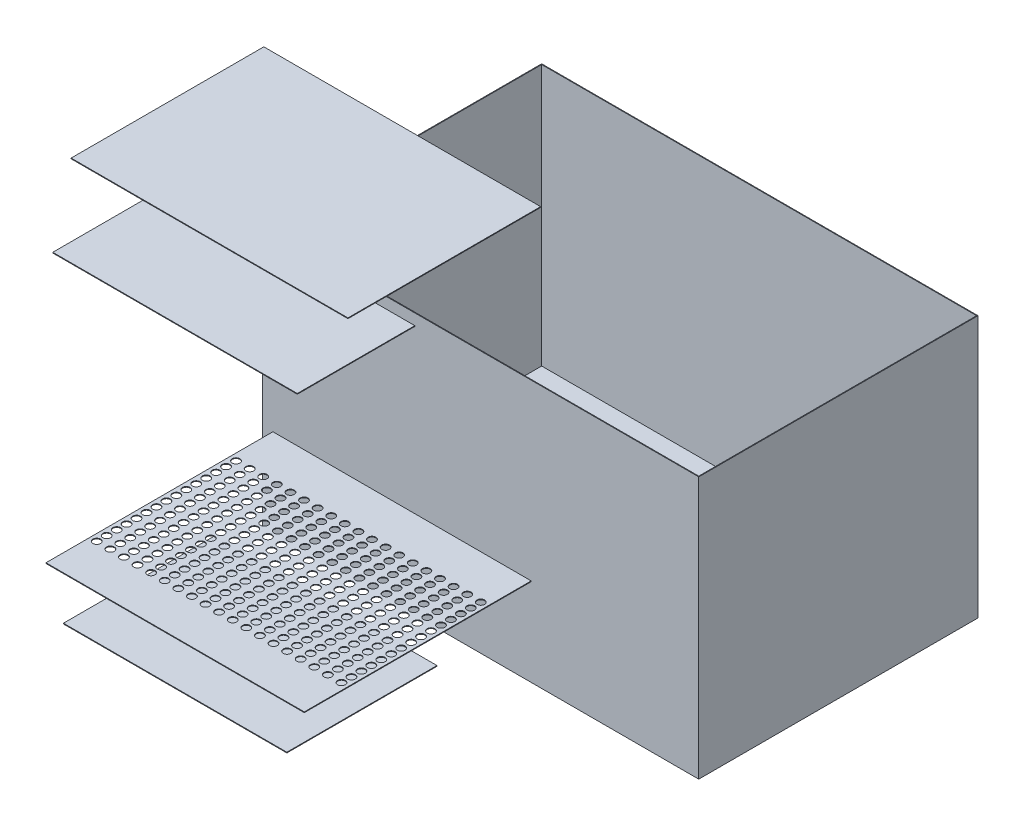
SolidWorks part; units mm, degrees
ref_plane "Спереди" through (0, 0, 0) normal (0, 0, 1) x (1, 0, 0)
ref_plane "Сверху" through (0, 0, 0) normal (0, 1, 0) x (1, 0, 0)
ref_plane "Справа" through (0, 0, 0) normal (1, 0, 0) x (0, 0, -1)
sketch "MASTER_FOOTPRINT" plane through (0, 0, 0) normal (0, 1, 0) x (1, 0, 0)
  line L1 (0, 0) -> (1250, 0)
  line L2 (0, 0) -> (0, 800)
  line L3 (0, 800) -> (1250, 800)
  line L4 (1250, 0) -> (1250, 800)
  dimension "D1" = 1250
  dimension "D2" = 800
extrude "BATH_BASE_PLATE" add sketch "MASTER_FOOTPRINT" along normal blind 750
shell "BATH_SHELL_2MM" thickness 2
sketch "Эскиз1" plane through (0, 0, 0) normal (0, 1, 0) x (1, 0, 0)
  line L1 (80, -220) -> (720, -220)
  line L2 (80, -220) -> (80, -650)
  line L3 (80, -650) -> (720, -650)
  line L4 (720, -220) -> (720, -650)
extrude "INLET_IMPACT_BAFFLE" add sketch "Эскиз1" along normal blind 2 from offset 125 separate body
sketch "Эскиз2" plane through (0, 0, 0) normal (0, 1, 0) x (1, 0, 0)
  line L0 (2, 2) -> (1248, 2) construction
  line L1 (30, 2) -> (770, 2)
  line L2 (30, 2) -> (30, -650)
  line L3 (30, -650) -> (770, -650)
  line L4 (770, 2) -> (770, -650)
  circle A0 centre (49.4737, -125) radius 11
  circle A1 centre (49.4737, -153.5) radius 11
  circle A2 centre (49.4737, -182) radius 11
  circle A3 centre (49.4737, -210.5) radius 11
  circle A4 centre (49.4737, -239) radius 11
  circle A5 centre (49.4737, -267.5) radius 11
  circle A6 centre (49.4737, -296) radius 11
  circle A7 centre (49.4737, -324.5) radius 11
  circle A8 centre (49.4737, -353) radius 11
  circle A9 centre (49.4737, -381.5) radius 11
  circle A10 centre (49.4737, -410) radius 11
  circle A11 centre (49.4737, -438.5) radius 11
  circle A12 centre (49.4737, -467) radius 11
  circle A13 centre (49.4737, -495.5) radius 11
  circle A14 centre (49.4737, -524) radius 11
  circle A15 centre (88.4211, -125) radius 11
  circle A16 centre (88.4211, -153.5) radius 11
  circle A17 centre (88.4211, -182) radius 11
  circle A18 centre (88.4211, -210.5) radius 11
  circle A19 centre (88.4211, -239) radius 11
  circle A20 centre (88.4211, -267.5) radius 11
  circle A21 centre (88.4211, -296) radius 11
  circle A22 centre (88.4211, -324.5) radius 11
  circle A23 centre (88.4211, -353) radius 11
  circle A24 centre (88.4211, -381.5) radius 11
  circle A25 centre (88.4211, -410) radius 11
  circle A26 centre (88.4211, -438.5) radius 11
  circle A27 centre (88.4211, -467) radius 11
  circle A28 centre (88.4211, -495.5) radius 11
  circle A29 centre (88.4211, -524) radius 11
  circle A30 centre (127.3684, -125) radius 11
  circle A31 centre (127.3684, -153.5) radius 11
  circle A32 centre (127.3684, -182) radius 11
  circle A33 centre (127.3684, -210.5) radius 11
  circle A34 centre (127.3684, -239) radius 11
  circle A35 centre (127.3684, -267.5) radius 11
  circle A36 centre (127.3684, -296) radius 11
  circle A37 centre (127.3684, -324.5) radius 11
  circle A38 centre (127.3684, -353) radius 11
  circle A39 centre (127.3684, -381.5) radius 11
  circle A40 centre (127.3684, -410) radius 11
  circle A41 centre (127.3684, -438.5) radius 11
  circle A42 centre (127.3684, -467) radius 11
  circle A43 centre (127.3684, -495.5) radius 11
  circle A44 centre (127.3684, -524) radius 11
  circle A45 centre (166.3158, -125) radius 11
  circle A46 centre (166.3158, -153.5) radius 11
  circle A47 centre (166.3158, -182) radius 11
  circle A48 centre (166.3158, -210.5) radius 11
  circle A49 centre (166.3158, -239) radius 11
  circle A50 centre (166.3158, -267.5) radius 11
  circle A51 centre (166.3158, -296) radius 11
  circle A52 centre (166.3158, -324.5) radius 11
  circle A53 centre (166.3158, -353) radius 11
  circle A54 centre (166.3158, -381.5) radius 11
  circle A55 centre (166.3158, -410) radius 11
  circle A56 centre (166.3158, -438.5) radius 11
  circle A57 centre (166.3158, -467) radius 11
  circle A58 centre (166.3158, -495.5) radius 11
  circle A59 centre (166.3158, -524) radius 11
  circle A60 centre (205.2632, -125) radius 11
  circle A61 centre (205.2632, -153.5) radius 11
  circle A62 centre (205.2632, -182) radius 11
  circle A63 centre (205.2632, -210.5) radius 11
  circle A64 centre (205.2632, -239) radius 11
  circle A65 centre (205.2632, -267.5) radius 11
  circle A66 centre (205.2632, -296) radius 11
  circle A67 centre (205.2632, -324.5) radius 11
  circle A68 centre (205.2632, -353) radius 11
  circle A69 centre (205.2632, -381.5) radius 11
  circle A70 centre (205.2632, -410) radius 11
  circle A71 centre (205.2632, -438.5) radius 11
  circle A72 centre (205.2632, -467) radius 11
  circle A73 centre (205.2632, -495.5) radius 11
  circle A74 centre (205.2632, -524) radius 11
  circle A75 centre (244.2105, -125) radius 11
  circle A76 centre (244.2105, -153.5) radius 11
  circle A77 centre (244.2105, -182) radius 11
  circle A78 centre (244.2105, -210.5) radius 11
  circle A79 centre (244.2105, -239) radius 11
  circle A80 centre (244.2105, -267.5) radius 11
  circle A81 centre (244.2105, -296) radius 11
  circle A82 centre (244.2105, -324.5) radius 11
  circle A83 centre (244.2105, -353) radius 11
  circle A84 centre (244.2105, -381.5) radius 11
  circle A85 centre (244.2105, -410) radius 11
  circle A86 centre (244.2105, -438.5) radius 11
  circle A87 centre (244.2105, -467) radius 11
  circle A88 centre (244.2105, -495.5) radius 11
  circle A89 centre (244.2105, -524) radius 11
  circle A90 centre (283.1579, -125) radius 11
  circle A91 centre (283.1579, -153.5) radius 11
  circle A92 centre (283.1579, -182) radius 11
  circle A93 centre (283.1579, -210.5) radius 11
  circle A94 centre (283.1579, -239) radius 11
  circle A95 centre (283.1579, -267.5) radius 11
  circle A96 centre (283.1579, -296) radius 11
  circle A97 centre (283.1579, -324.5) radius 11
  circle A98 centre (283.1579, -353) radius 11
  circle A99 centre (283.1579, -381.5) radius 11
  circle A100 centre (283.1579, -410) radius 11
  circle A101 centre (283.1579, -438.5) radius 11
  circle A102 centre (283.1579, -467) radius 11
  circle A103 centre (283.1579, -495.5) radius 11
  circle A104 centre (283.1579, -524) radius 11
  circle A105 centre (322.1053, -125) radius 11
  circle A106 centre (322.1053, -153.5) radius 11
  circle A107 centre (322.1053, -182) radius 11
  circle A108 centre (322.1053, -210.5) radius 11
  circle A109 centre (322.1053, -239) radius 11
  circle A110 centre (322.1053, -267.5) radius 11
  circle A111 centre (322.1053, -296) radius 11
  circle A112 centre (322.1053, -324.5) radius 11
  circle A113 centre (322.1053, -353) radius 11
  circle A114 centre (322.1053, -381.5) radius 11
  circle A115 centre (322.1053, -410) radius 11
  circle A116 centre (322.1053, -438.5) radius 11
  circle A117 centre (322.1053, -467) radius 11
  circle A118 centre (322.1053, -495.5) radius 11
  circle A119 centre (322.1053, -524) radius 11
  circle A120 centre (361.0526, -125) radius 11
  circle A121 centre (361.0526, -153.5) radius 11
  circle A122 centre (361.0526, -182) radius 11
  circle A123 centre (361.0526, -210.5) radius 11
  circle A124 centre (361.0526, -239) radius 11
  circle A125 centre (361.0526, -267.5) radius 11
  circle A126 centre (361.0526, -296) radius 11
  circle A127 centre (361.0526, -324.5) radius 11
  circle A128 centre (361.0526, -353) radius 11
  circle A129 centre (361.0526, -381.5) radius 11
  circle A130 centre (361.0526, -410) radius 11
  circle A131 centre (361.0526, -438.5) radius 11
  circle A132 centre (361.0526, -467) radius 11
  circle A133 centre (361.0526, -495.5) radius 11
  circle A134 centre (361.0526, -524) radius 11
  circle A135 centre (400, -125) radius 11
  circle A136 centre (400, -153.5) radius 11
  circle A137 centre (400, -182) radius 11
  circle A138 centre (400, -210.5) radius 11
  circle A139 centre (400, -239) radius 11
  circle A140 centre (400, -267.5) radius 11
  circle A141 centre (400, -296) radius 11
  circle A142 centre (400, -324.5) radius 11
  circle A143 centre (400, -353) radius 11
  circle A144 centre (400, -381.5) radius 11
  circle A145 centre (400, -410) radius 11
  circle A146 centre (400, -438.5) radius 11
  circle A147 centre (400, -467) radius 11
  circle A148 centre (400, -495.5) radius 11
  circle A149 centre (400, -524) radius 11
  circle A150 centre (438.9474, -125) radius 11
  circle A151 centre (438.9474, -153.5) radius 11
  circle A152 centre (438.9474, -182) radius 11
  circle A153 centre (438.9474, -210.5) radius 11
  circle A154 centre (438.9474, -239) radius 11
  circle A155 centre (438.9474, -267.5) radius 11
  circle A156 centre (438.9474, -296) radius 11
  circle A157 centre (438.9474, -324.5) radius 11
  circle A158 centre (438.9474, -353) radius 11
  circle A159 centre (438.9474, -381.5) radius 11
  circle A160 centre (438.9474, -410) radius 11
  circle A161 centre (438.9474, -438.5) radius 11
  circle A162 centre (438.9474, -467) radius 11
  circle A163 centre (438.9474, -495.5) radius 11
  circle A164 centre (438.9474, -524) radius 11
  circle A165 centre (477.8947, -125) radius 11
  circle A166 centre (477.8947, -153.5) radius 11
  circle A167 centre (477.8947, -182) radius 11
  circle A168 centre (477.8947, -210.5) radius 11
  circle A169 centre (477.8947, -239) radius 11
  circle A170 centre (477.8947, -267.5) radius 11
  circle A171 centre (477.8947, -296) radius 11
  circle A172 centre (477.8947, -324.5) radius 11
  circle A173 centre (477.8947, -353) radius 11
  circle A174 centre (477.8947, -381.5) radius 11
  circle A175 centre (477.8947, -410) radius 11
  circle A176 centre (477.8947, -438.5) radius 11
  circle A177 centre (477.8947, -467) radius 11
  circle A178 centre (477.8947, -495.5) radius 11
  circle A179 centre (477.8947, -524) radius 11
  circle A180 centre (516.8421, -125) radius 11
  circle A181 centre (516.8421, -153.5) radius 11
  circle A182 centre (516.8421, -182) radius 11
  circle A183 centre (516.8421, -210.5) radius 11
  circle A184 centre (516.8421, -239) radius 11
  circle A185 centre (516.8421, -267.5) radius 11
  circle A186 centre (516.8421, -296) radius 11
  circle A187 centre (516.8421, -324.5) radius 11
  circle A188 centre (516.8421, -353) radius 11
  circle A189 centre (516.8421, -381.5) radius 11
  circle A190 centre (516.8421, -410) radius 11
  circle A191 centre (516.8421, -438.5) radius 11
  circle A192 centre (516.8421, -467) radius 11
  circle A193 centre (516.8421, -495.5) radius 11
  circle A194 centre (516.8421, -524) radius 11
  circle A195 centre (555.7895, -125) radius 11
  circle A196 centre (555.7895, -153.5) radius 11
  circle A197 centre (555.7895, -182) radius 11
  circle A198 centre (555.7895, -210.5) radius 11
  circle A199 centre (555.7895, -239) radius 11
  circle A200 centre (555.7895, -267.5) radius 11
  circle A201 centre (555.7895, -296) radius 11
  circle A202 centre (555.7895, -324.5) radius 11
  circle A203 centre (555.7895, -353) radius 11
  circle A204 centre (555.7895, -381.5) radius 11
  circle A205 centre (555.7895, -410) radius 11
  circle A206 centre (555.7895, -438.5) radius 11
  circle A207 centre (555.7895, -467) radius 11
  circle A208 centre (555.7895, -495.5) radius 11
  circle A209 centre (555.7895, -524) radius 11
  circle A210 centre (594.7368, -125) radius 11
  circle A211 centre (594.7368, -153.5) radius 11
  circle A212 centre (594.7368, -182) radius 11
  circle A213 centre (594.7368, -210.5) radius 11
  circle A214 centre (594.7368, -239) radius 11
  circle A215 centre (594.7368, -267.5) radius 11
  circle A216 centre (594.7368, -296) radius 11
  circle A217 centre (594.7368, -324.5) radius 11
  circle A218 centre (594.7368, -353) radius 11
  circle A219 centre (594.7368, -381.5) radius 11
  circle A220 centre (594.7368, -410) radius 11
  circle A221 centre (594.7368, -438.5) radius 11
  circle A222 centre (594.7368, -467) radius 11
  circle A223 centre (594.7368, -495.5) radius 11
  circle A224 centre (594.7368, -524) radius 11
  circle A225 centre (633.6842, -125) radius 11
  circle A226 centre (633.6842, -153.5) radius 11
  circle A227 centre (633.6842, -182) radius 11
  circle A228 centre (633.6842, -210.5) radius 11
  circle A229 centre (633.6842, -239) radius 11
  circle A230 centre (633.6842, -267.5) radius 11
  circle A231 centre (633.6842, -296) radius 11
  circle A232 centre (633.6842, -324.5) radius 11
  circle A233 centre (633.6842, -353) radius 11
  circle A234 centre (633.6842, -381.5) radius 11
  circle A235 centre (633.6842, -410) radius 11
  circle A236 centre (633.6842, -438.5) radius 11
  circle A237 centre (633.6842, -467) radius 11
  circle A238 centre (633.6842, -495.5) radius 11
  circle A239 centre (633.6842, -524) radius 11
  circle A240 centre (672.6316, -125) radius 11
  circle A241 centre (672.6316, -153.5) radius 11
  circle A242 centre (672.6316, -182) radius 11
  circle A243 centre (672.6316, -210.5) radius 11
  circle A244 centre (672.6316, -239) radius 11
  circle A245 centre (672.6316, -267.5) radius 11
  circle A246 centre (672.6316, -296) radius 11
  circle A247 centre (672.6316, -324.5) radius 11
  circle A248 centre (672.6316, -353) radius 11
  circle A249 centre (672.6316, -381.5) radius 11
  circle A250 centre (672.6316, -410) radius 11
  circle A251 centre (672.6316, -438.5) radius 11
  circle A252 centre (672.6316, -467) radius 11
  circle A253 centre (672.6316, -495.5) radius 11
  circle A254 centre (672.6316, -524) radius 11
  circle A255 centre (711.5789, -125) radius 11
  circle A256 centre (711.5789, -153.5) radius 11
  circle A257 centre (711.5789, -182) radius 11
  circle A258 centre (711.5789, -210.5) radius 11
  circle A259 centre (711.5789, -239) radius 11
  circle A260 centre (711.5789, -267.5) radius 11
  circle A261 centre (711.5789, -296) radius 11
  circle A262 centre (711.5789, -324.5) radius 11
  circle A263 centre (711.5789, -353) radius 11
  circle A264 centre (711.5789, -381.5) radius 11
  circle A265 centre (711.5789, -410) radius 11
  circle A266 centre (711.5789, -438.5) radius 11
  circle A267 centre (711.5789, -467) radius 11
  circle A268 centre (711.5789, -495.5) radius 11
  circle A269 centre (711.5789, -524) radius 11
  circle A270 centre (750.5263, -125) radius 11
  circle A271 centre (750.5263, -153.5) radius 11
  circle A272 centre (750.5263, -182) radius 11
  circle A273 centre (750.5263, -210.5) radius 11
  circle A274 centre (750.5263, -239) radius 11
  circle A275 centre (750.5263, -267.5) radius 11
  circle A276 centre (750.5263, -296) radius 11
  circle A277 centre (750.5263, -324.5) radius 11
  circle A278 centre (750.5263, -353) radius 11
  circle A279 centre (750.5263, -381.5) radius 11
  circle A280 centre (750.5263, -410) radius 11
  circle A281 centre (750.5263, -438.5) radius 11
  circle A282 centre (750.5263, -467) radius 11
  circle A283 centre (750.5263, -495.5) radius 11
  circle A284 centre (750.5263, -524) radius 11
extrude "DISTRIBUTOR_D22" add sketch "Эскиз2" along normal blind 2 from offset 250 separate body
sketch "Эскиз3" plane through (0, 0, 0) normal (0, 1, 0) x (1, 0, 0)
  line L0 (30, -650) -> (770, -650) construction
  line L1 (49.4737, -313.5) -> (750, -313.5)
  line L2 (49.4737, -313.5) -> (49.4737, -650)
  line L3 (49.4737, -650) -> (750, -650)
  line L4 (750, -313.5) -> (750, -650)
  circle A0 centre (49.4737, -324.5) radius 11 construction
extrude "OUTLET_SUBMERGED_BAFFLE" add sketch "Эскиз3" along normal blind 2 from offset 1030 separate body
sketch "Эскиз4" plane through (0, 0, 0) normal (0, 1, 0) x (1, 0, 0)
  line L1 (2, 2) -> (795, 2)
  line L2 (2, 2) -> (2, -550)
  line L3 (2, -550) -> (795, -550)
  line L4 (795, 2) -> (795, -550)
extrude "OVERFLOW_WEIR_Z550" add sketch "Эскиз4" along normal blind 2 from offset 1190 separate body
equation "\"AI_Q_Peak\"= 0.006"
equation "\"AI_B_Bath\" = 800"
equation "\"AI_L_Settle\" = 800"
equation "\"AI_L_Inlet\"= 250"
equation "\"AI_L_Outlet\"= 200"
equation "\"AI_L_Bath\" = 1250"
equation "\"AI_H_Water\"= 550"
equation "\"AI_H_Freeboard\"= 200"
equation "\"AI_H_Bath\"= 750"
equation "\"AI_Shell_Thickness\"= 2"
equation "\"AI_Inlet_DN\"= 100"
equation "\"AI_Weir_Width\"= 600"
equation "\"AI_Inlet_Baffle_Offset\"= 125"
equation "\"AI_Distributor_Open_Area\"= 0.28"
equation "\"AI_Distributor_Hole_Dia\"= 22"
equation "\"AI_Distributor_Blind_Zone\"= 110"
equation "\"AI_Outlet_Baffle_Depth\"= 250"
equation "\"AI_Screw_Diameter\"= 100"
equation "\"AI_Screw_Pitch\"= 100"
equation "\"AI_Screw_Angle\"= 30"
equation "\"AI_Screw_Rpm\"= 15"
equation "\"AI_Screw_Clearance\"= 5"
equation "\"AI_Liner_Thickness\"= 5"
equation "\"AI_Discharge_Height\"= 650"
equation "\"AI_Frame_Height\"= 500"
equation "\"D1@MASTER_FOOTPRINT\" = \"AI_L_Bath\""
equation "\"D2@MASTER_FOOTPRINT\" = \"AI_B_Bath\""
equation "\"D1@BATH_BASE_PLATE\" = \"AI_H_Bath\""
